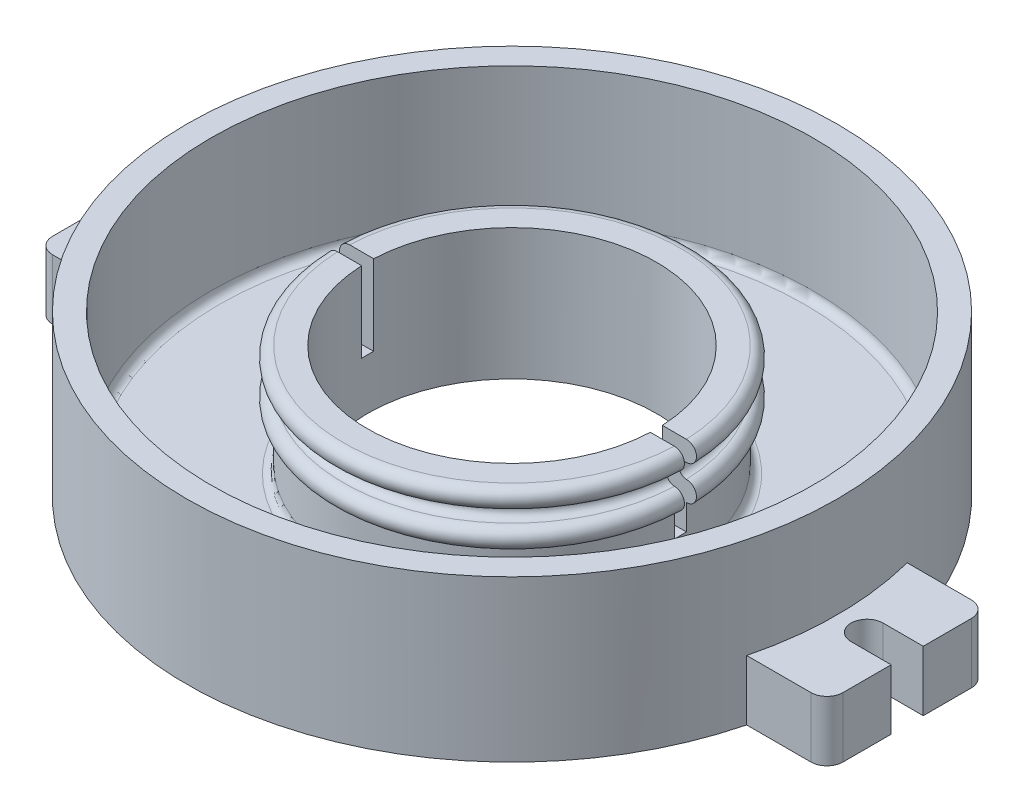
SolidWorks part; units mm, degrees
ref_plane "Front Plane" through (0, 0, 0) normal (0, 0, 1) x (1, 0, 0)
ref_plane "Top Plane" through (0, 0, 0) normal (0, 1, 0) x (1, 0, 0)
ref_plane "Right Plane" through (0, 0, 0) normal (1, 0, 0) x (0, 0, -1)
sketch "Sketch2" plane through (0, 0, 0) normal (0, 0, 1) x (1, 0, 0)
  line L0 (0, 0) -> (0, 40)
  line L3 (6, 5) -> (39, 5)
  line L6 (45, 32.6603) -> (45, 0)
  line L7 (45, 0) -> (0, 0)
  line L8 (81, 93.5377) -> (81, -39.7642) construction
  line L10 (6, 40) -> (6, 5)
  line L11 (22.5, -4.4333) -> (22.5, 86.2524) construction
  line L12 (39, 19) -> (39, 5)
  line L13 (45, 32.6603) -> (39, 32.6603)
  line L14 (0, 40) -> (6, 40)
  arc A5 (39, 19) -> (39, 24) centre (39, 21.5) cw
  arc A6 (39, 27.6603) -> (39, 24) centre (39, 25.8301) cw
  arc A7 (39, 27.6603) -> (39, 32.6603) centre (39, 30.1603) cw
  dimension "D8" = 1.8301
  dimension "D11" = 4.3301
  dimension "D12" = 3.6603
  dimension "D15" = 6
  dimension "D9" = 2.5
  dimension "D17" = 2.5
  dimension "D3" = 2.5
  dimension "D1" = 14
  dimension "D2" = 40
  dimension "D4" = 5
  dimension "D5" = 6
  dimension "D6" = 45
  dimension "D7" = 36
  dimension "D10" = 4.3301
  dimension "D13" = 13.6603
  dimension "D14" = 6.8301
  dimension "D16" = 6
revolve "Revolve1" add sketch "Sketch2" angle 360 about L8
sketch "Sketch3" plane through (0, 0, 0) normal (0, -1, 0) x (1, 0, 0)
  line L0 (-46.2472, 0) -> (238.3544, 0) construction
  line L1 (-17.492, 16) -> (-17.492, 4)
  line L2 (-13.492, -20) -> (2.508, -20)
  line L3 (-13.492, 20) -> (2.508, 20)
  line L4 (-7.492, 4) -> (-17.492, 4)
  line L5 (-7.492, -4) -> (-17.492, -4)
  line L6 (-17.492, -4) -> (-17.492, -16)
  line L7 (81, 112.7412) -> (81, -119.1481) construction
  line L8 (209.7496, -20) -> (159.492, -20)
  line L9 (211.0341, -12.1881) -> (210.6195, -12.0957)
  line L10 (175.492, -20) -> (159.492, -20)
  line L11 (179.492, -4) -> (179.492, -16)
  line L12 (169.492, -4) -> (179.492, -4)
  line L13 (169.492, 4) -> (179.492, 4)
  line L14 (179.492, 16) -> (179.492, 4)
  line L15 (175.492, 20) -> (159.492, 20)
  circle A0 centre (81, 0) radius 81 construction
  arc A1 (2.508, 20) -> (2.508, -20) centre (81, 0) ccw
  arc A2 (-7.492, -4) -> (-7.492, 4) centre (-7.492, 0) ccw
  arc A3 (179.492, -16) -> (175.492, -20) centre (175.492, -16) cw
  arc A4 (159.492, -20) -> (159.492, 20) centre (81, 0) ccw
  arc A5 (169.492, -4) -> (169.492, 4) centre (169.492, 0) cw
  arc A6 (175.492, 20) -> (179.492, 16) centre (175.492, 16) cw
  arc A7 (-17.492, -16) -> (-13.492, -20) centre (-13.492, -16) ccw
  arc A8 (-13.492, 20) -> (-17.492, 16) centre (-13.492, 16) ccw
  point P37 (-17.492, -20)
  point P40 (-17.492, 20)
  dimension "D3" = 4
  dimension "D5" = 20
  dimension "D6" = 4
  dimension "D1" = 20
  dimension "D2" = 20
  dimension "D4" = 10
extrude "Boss-Extrude1" add sketch "Sketch3" against normal blind 15
fillet "Fillet3" radius 2 2 edges at (39, 5, 0) (6, 5, 0)
sketch "Sketch4" plane through (0, 32.6603, 0) normal (0, 1, 0) x (1, 0, 0)
  line L0 (36.6714, 0) -> (137.8671, 0) construction
  line L2 (21, 1.5) -> (141, 1.5)
  line L3 (21, 1.5) -> (21, -1.5)
  line L4 (21, -1.5) -> (141, -1.5)
  line L5 (141, 1.5) -> (141, -1.5)
  circle A0 centre (81, 0) radius 36 construction
  dimension "D4" = 60
  dimension "D1" = 3
  dimension "D2" = 1.5
  dimension "D3" = 120
extrude "Cut-Extrude1" cut sketch "Sketch4" against normal blind 20
sketch "Sketch5" plane through (0, 5, 0) normal (0, 1, 0) x (1, 0, 0)
  line L0 (-50.8957, 0) -> (234.476, 0) construction
  line L1 (81, 95.213) -> (81, -124.9308) construction
  line L2 (61, -53.8) -> (101, -53.8)
  line L3 (101, -53.8) -> (101, -45)
  line L6 (101, -45) -> (61, -45)
  line L9 (61, -45) -> (61, -53.8)
  arc A0 (45.0313, 1.5) -> (45.0313, -1.5) centre (81, 0) ccw construction
  arc A1 (116.9687, -1.5) -> (116.9687, 1.5) centre (81, 0) ccw construction
  arc A2 (45.0313, -1.5) -> (116.9687, -1.5) centre (81, 0) ccw construction
  arc A3 (116.9687, 1.5) -> (45.0313, 1.5) centre (81, 0) ccw construction
  arc A4 (45.0313, 1.5) -> (45.0313, -1.5) centre (81, 0) ccw
  arc A5 (116.9687, -1.5) -> (116.9687, 1.5) centre (81, 0) ccw
  arc A6 (45.0313, -1.5) -> (116.9687, -1.5) centre (81, 0) ccw
  arc A7 (116.9687, 1.5) -> (45.0313, 1.5) centre (81, 0) ccw
  point P5 (81, -45)
  dimension "D1" = 8.8
  dimension "D2" = 40
  dimension "D7" = 45
extrude "Cut-Extrude2" cut sketch "Sketch5" against normal blind 10 contours A4 A6 A5 A7 | L2 L3 L6 L9
